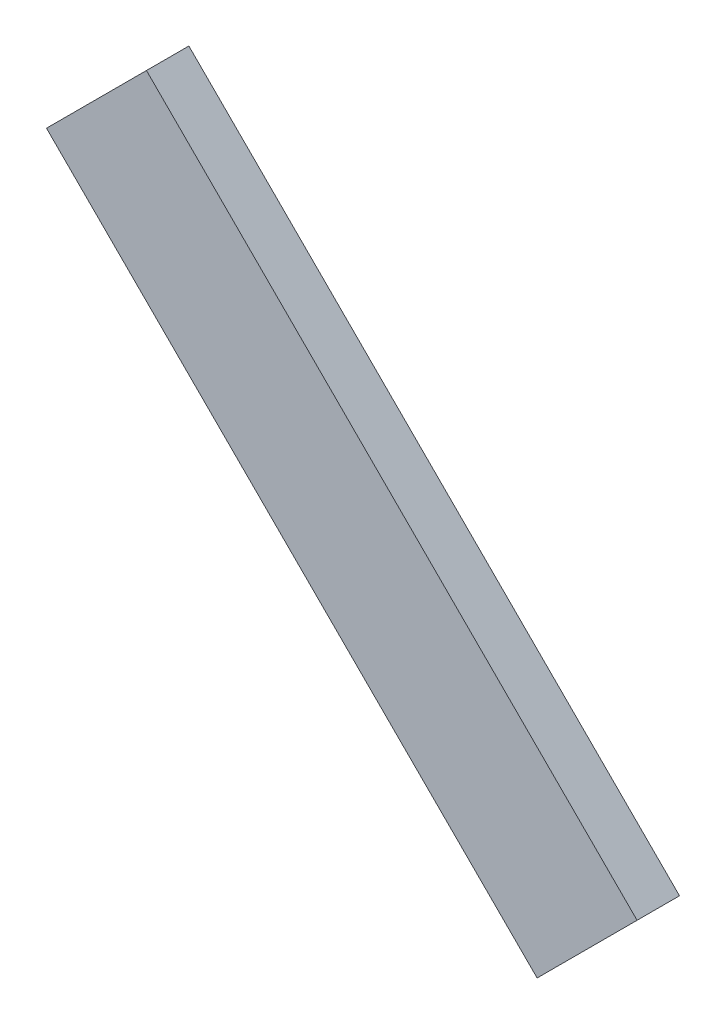
SolidWorks part; units mm, degrees
ref_plane "前基準面" through (0, 0, 0) normal (0, 0, 1) x (1, 0, 0)
ref_plane "上基準面" through (0, 0, 0) normal (0, 1, 0) x (1, 0, 0)
ref_plane "右基準面" through (0, 0, 0) normal (1, 0, 0) x (0, 0, -1)
sketch "草圖1" plane through (0, 0, 0) normal (0, 0, 1) x (1, 0, 0)
  line L0 (105.9228, 85.3462) -> (140.6276, 50.6414) construction
  line L1 (105.9228, 85.3462) -> (140.6276, 50.6414)
  line L2 (105.9228, 85.3462) -> (98.8518, 78.2751)
  line L3 (98.8518, 78.2751) -> (133.5566, 43.5703)
  line L4 (133.5566, 43.5703) -> (140.6276, 50.6414)
extrude "填料-伸長1" add sketch "草圖1" along normal blind 3
